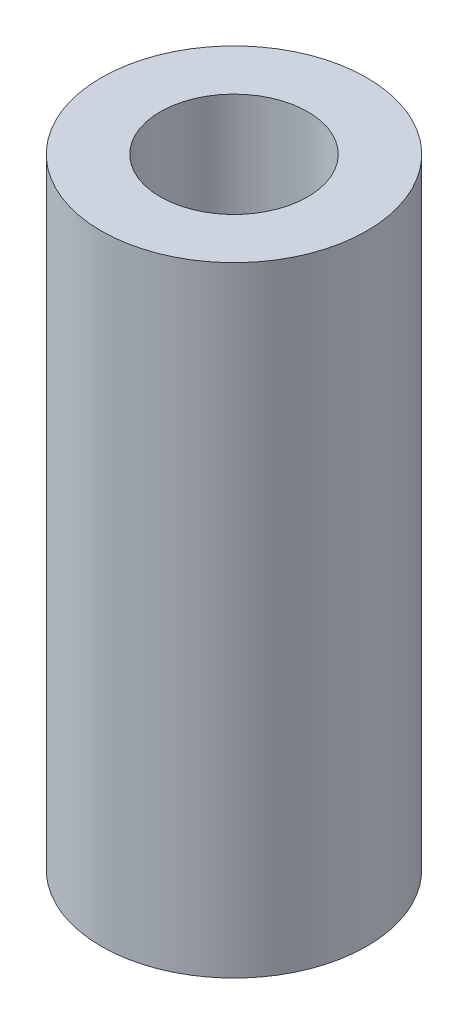
SolidWorks part; units mm, degrees
ref_plane "Front" through (0, 0, 0) normal (0, 0, 1) x (1, 0, 0)
ref_plane "Top" through (0, 0, 0) normal (0, 1, 0) x (1, 0, 0)
ref_plane "Right" through (0, 0, 0) normal (1, 0, 0) x (0, 0, -1)
sketch "Sketch1" plane through (0, 0, 0) normal (0, 1, 0) x (1, 0, 0)
  circle A0 centre (0, 0) radius 2.25
  dimension "D1" = 4.5
extrude "Boss-Extrude1" add sketch "Sketch1" along normal blind 10.5
sketch "Sketch2" plane through (0, 10.5, 0) normal (0, 1, 0) x (1, 0, 0)
  circle A0 centre (0, 0) radius 1.25
  dimension "D1" = 2.5
extrude "Cut-Extrude1" cut sketch "Sketch2" against normal up to next
